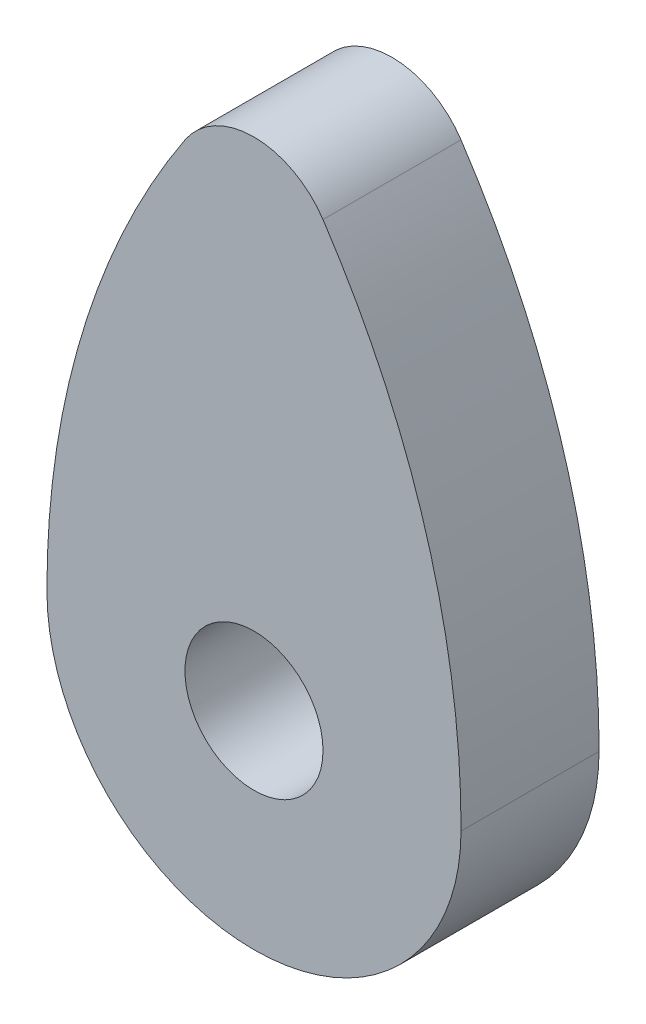
SolidWorks part; units mm, degrees
ref_plane "Front Plane" through (0, 0, 0) normal (0, 0, 1) x (1, 0, 0)
ref_plane "Top Plane" through (0, 0, 0) normal (0, 1, 0) x (1, 0, 0)
ref_plane "Right Plane" through (0, 0, 0) normal (1, 0, 0) x (0, 0, -1)
sketch "Sketch1" plane through (0, 0, 0) normal (0, 0, 1) x (1, 0, 0)
  line L0 (0, 0) -> (0, 5) construction
  line L1 (0, 15) -> (0, 30) construction
  circle A0 centre (0, 0) radius 5
  arc A1 (-14.9999, -0.05) -> (14.9999, -0.05) centre (0, 0) ccw
  arc A2 (5, 33.3167) -> (-5, 33.3167) centre (0, 30) ccw
  arc A3 (-5, 33.3167) -> (-14.9999, -0.05) centre (44.9997, 0.15) ccw
  arc A4 (5, 33.3167) -> (14.9999, -0.05) centre (-44.9997, 0.15) cw
  point P9 (0, 0)
  dimension "D1" = 10
  dimension "D2" = 30
  dimension "D3" = 12
  dimension "D5" = 60
  dimension "D4" = 30
extrude "Boss-Extrude1" add sketch "Sketch1" along normal mid plane 10
